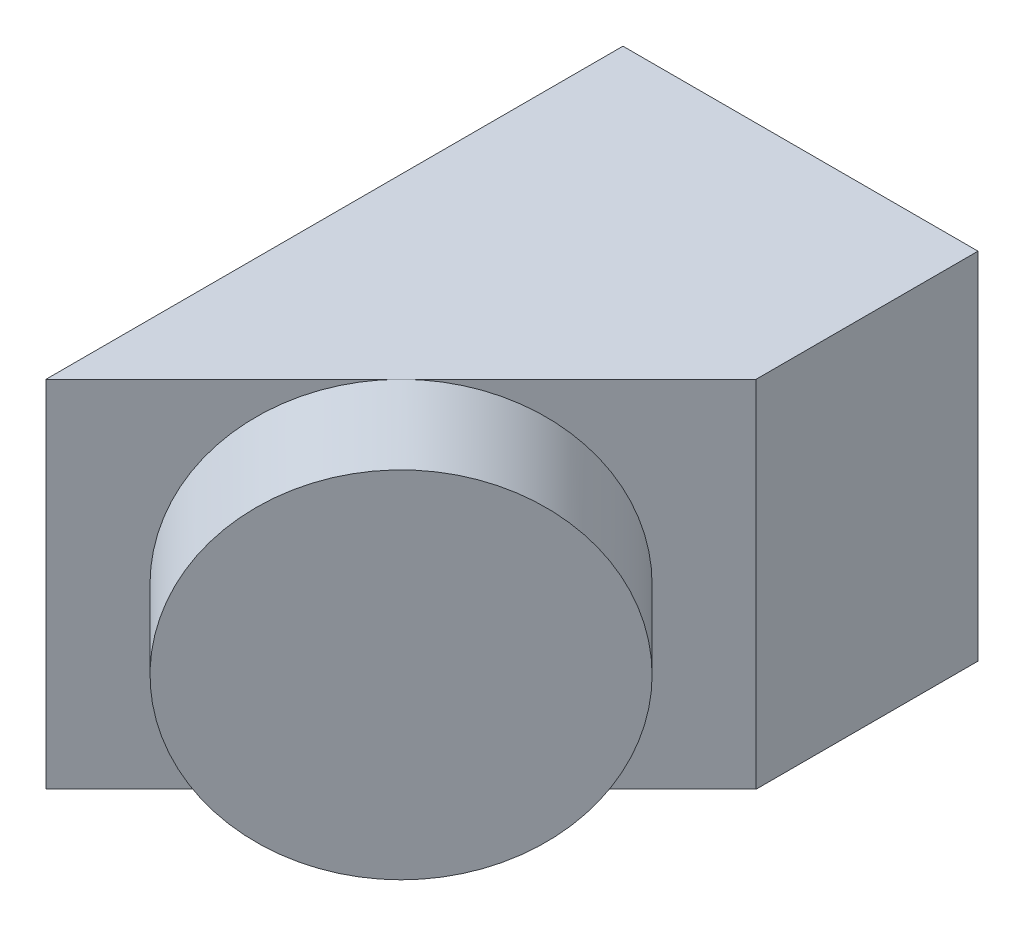
SolidWorks part; units mm, degrees
ref_plane "前视基准面" through (0, 0, 0) normal (0, 0, 1) x (1, 0, 0)
ref_plane "上视基准面" through (0, 0, 0) normal (0, 1, 0) x (1, 0, 0)
ref_plane "右视基准面" through (0, 0, 0) normal (1, 0, 0) x (0, 0, -1)
sketch "草图1" plane through (0, 0, 0) normal (0, 0, 1) x (1, 0, 0)
  line L1 (0, 0) -> (16, 0)
  line L2 (0, 0) -> (0, 16)
  line L3 (0, 16) -> (16, 16)
  line L4 (16, 0) -> (16, 16)
  line L5 (3, 3) -> (13, 3)
  line L6 (3, 3) -> (3, 13)
  line L7 (3, 13) -> (13, 13)
  line L8 (13, 3) -> (13, 13)
  point P5 (3, 3)
  point P10 (0, 0)
  point P11 (0, 0)
extrude "凸台-拉伸1" add sketch "草图1" along normal blind 10
sketch "草图2" plane through (0, 0, 0) normal (0, -1, 0) x (1, 0, 0)
  line L0 (0, 10) -> (0, 26)
  line L1 (0, 26) -> (16, 10)
  line L2 (16, 10) -> (0, 10)
sketch "草图5" plane through (0, 0, 0) normal (0, 0, -1) x (-1, 0, 0)
  line L1 (-3, 3) -> (-13, 3)
  line L2 (-3, 3) -> (-3, 13)
  line L3 (-3, 13) -> (-13, 13)
  line L4 (-13, 3) -> (-13, 13)
extrude "凸台-拉伸2" add sketch "草图2" against normal blind 16
sketch "草图6" plane through (13, 0, 13) normal (0.7071, 0, 0.7071) x (0.7071, 0, -0.7071)
  line L0 (-7.0711, 0) -> (-7.0711, 16)
  line L1 (4.2426, 0) -> (-18.3848, 0) construction
  line L2 (4.2426, 16) -> (-18.3848, 16) construction
  circle A0 centre (-7.0711, 8) radius 8
extrude "凸台-拉伸3" add sketch "草图6" along normal blind 5 contours L0 A0 | L0 A0
